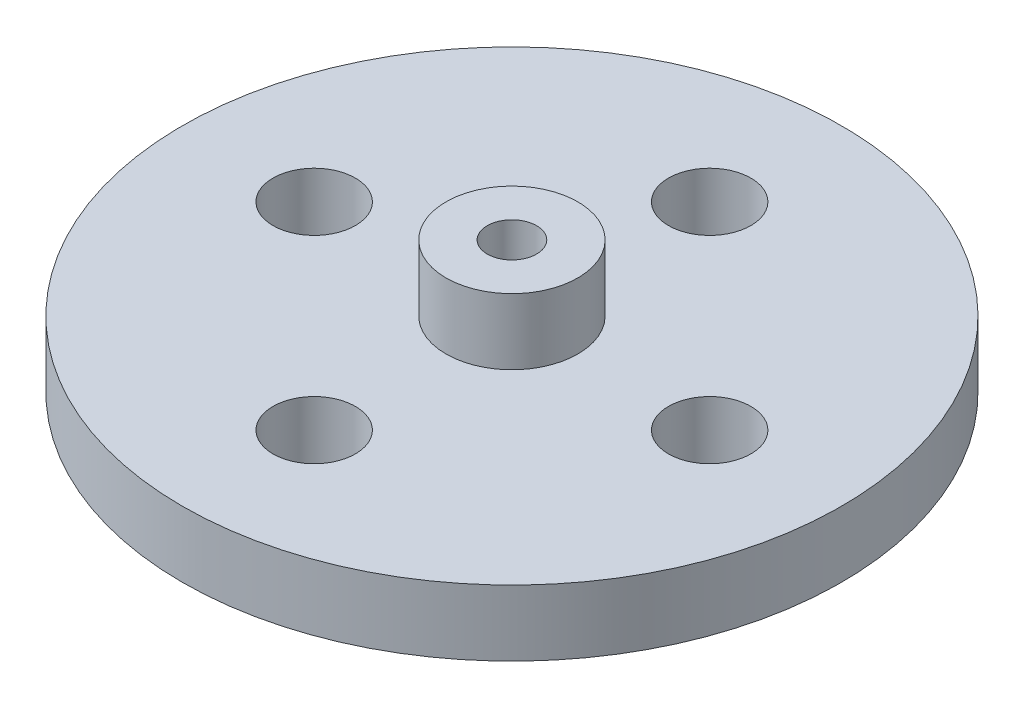
SolidWorks part; units mm, degrees
ref_plane "Front Plane" through (0, 0, 0) normal (0, 0, 1) x (1, 0, 0)
ref_plane "Top Plane" through (0, 0, 0) normal (0, 1, 0) x (1, 0, 0)
ref_plane "Right Plane" through (0, 0, 0) normal (1, 0, 0) x (0, 0, -1)
sketch "Sketch1" plane through (0, 0, 0) normal (0, 1, 0) x (1, 0, 0)
  circle A0 centre (0, 0) radius 31.75
  dimension "D1" = 63.5
extrude "Boss-Extrude1" add sketch "Sketch1" along normal blind 6.35
sketch "Sketch2" plane through (0, 6.35, 0) normal (0, 1, 0) x (1, 0, 0)
  circle A6 centre (0, 0) radius 6.35
  point P15 (0, 0)
  dimension "D4" = 12.7
extrude "Boss-Extrude2" add sketch "Sketch2" along normal blind 6.35
sketch "Sketch3" plane through (0, 12.7, 0) normal (0, 1, 0) x (1, 0, 0)
  circle A0 centre (0, 0) radius 2.3749
  arc A1 (1.4908, 1.8487) -> (1.866, -1.4691) centre (0, 0) ccw construction
extrude "Cut-Extrude1" cut sketch "Sketch3" against normal through all
hole_wizard "3/8-16 Tapped Hole1" positions "Sketch5" profile "Sketch4" tap size "3/8-16" standard "ANSI Inch"
sketch "Sketch5" plane through (0, 6.35, 0) normal (0, 1, 0) x (1, 0, 0)
  point P0 (0, 19.05)
  point P11 (19.05, 0)
  point P12 (0, -19.05)
  point P13 (-19.05, 0)
  dimension "D1" = 19.05
  dimension "D2" = 4
sketch "Sketch4" plane through (0, 6.35, -19.05) normal (1, 0, 0) x (0, 0, 1)
  line L0 (0, 0) -> (0, 29.3087)
  line L1 (0, 29.3087) -> (3.9687, 26.924)
  line L2 (3.9687, 26.924) -> (3.9687, 0)
  line L5 (3.9687, 0) -> (0, 0)
  line L10 (0, 29.3087) -> (-3.9688, 26.924) construction
  line L11 (0, -6.35) -> (0, 107.95) construction
  dimension "Tap Drill Dia." = 7.9375
  dimension "Tap Drill Depth" = 26.924
  dimension "Drill Angle" = 118
cosmetic thread "Hole Thread1" parameters "D1"=6.35, "D2"=9.525
cosmetic thread "Hole Thread3" parameters "D1"=6.35, "D2"=9.525
cosmetic thread "Hole Thread4" parameters "D1"=6.35, "D2"=9.525
cosmetic thread "Hole Thread5" parameters "D1"=6.35, "D2"=9.525
